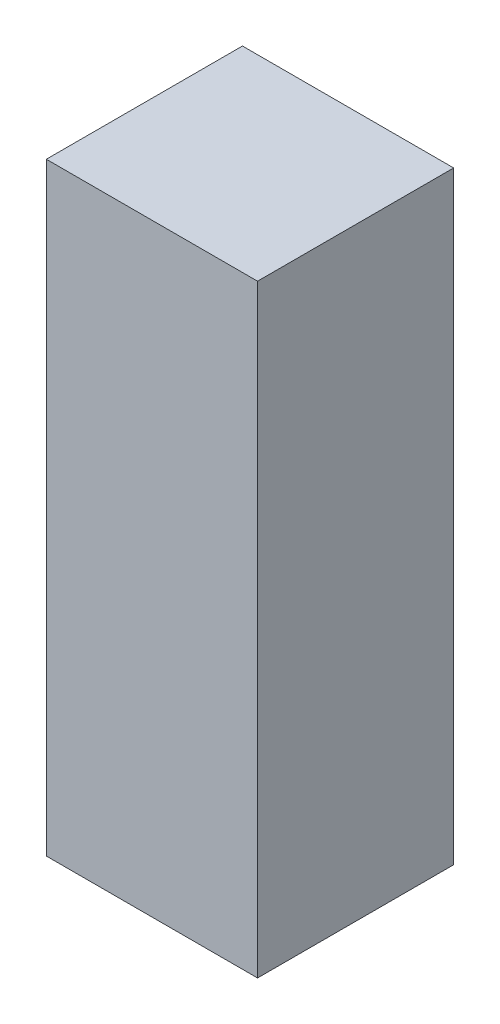
SolidWorks part; units mm, degrees
ref_plane "Front Plane" through (0, 0, 0) normal (0, 0, 1) x (1, 0, 0)
ref_plane "Top Plane" through (0, 0, 0) normal (0, 1, 0) x (1, 0, 0)
ref_plane "Right Plane" through (0, 0, 0) normal (1, 0, 0) x (0, 0, -1)
other "Configuration Table"
sketch "Sketch1" plane through (0, 0, 0) normal (0, 0, 1) x (1, 0, 0)
  line L1 (24, 1080) -> (38, 1080)
  line L2 (24, 1080) -> (24, 1120)
  line L3 (24, 1120) -> (38, 1120)
  line L4 (38, 1080) -> (38, 1120)
extrude "PACK_sarjor_kapisi_mentese_1_1" add sketch "Sketch1" along normal blind 13 from offset 20 separate body
